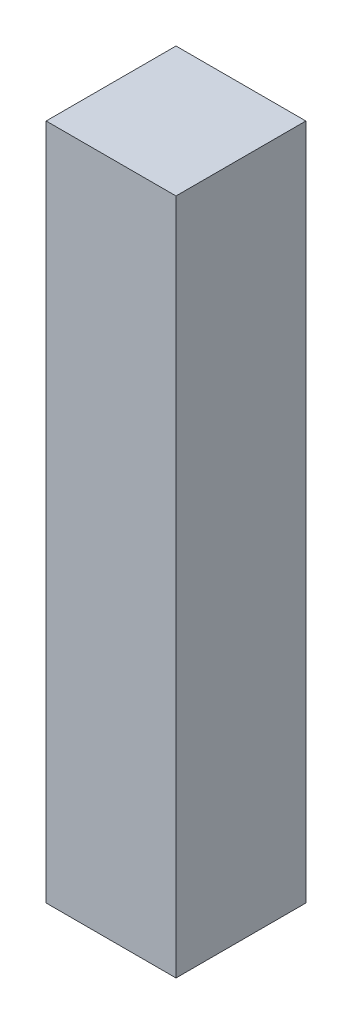
SolidWorks part; units mm, degrees
material "Malleable Cast Iron"
ref_plane "Front Plane" through (0, 0, 0) normal (0, 0, 1) x (1, 0, 0)
ref_plane "Top Plane" through (0, 0, 0) normal (0, 1, 0) x (1, 0, 0)
ref_plane "Right Plane" through (0, 0, 0) normal (1, 0, 0) x (0, 0, -1)
sketch "Sketch1" plane through (0, 0, 0) normal (0, 1, 0) x (1, 0, 0)
  line L1 (0, 0) -> (7.9, 0)
  line L2 (0, 0) -> (0, 7.9)
  line L3 (0, 7.9) -> (7.9, 7.9)
  line L4 (7.9, 0) -> (7.9, 7.9)
  dimension "D1" = 7.9
  dimension "D2" = 7.9
extrude "Boss-Extrude1" add sketch "Sketch1" along normal blind 41.2
